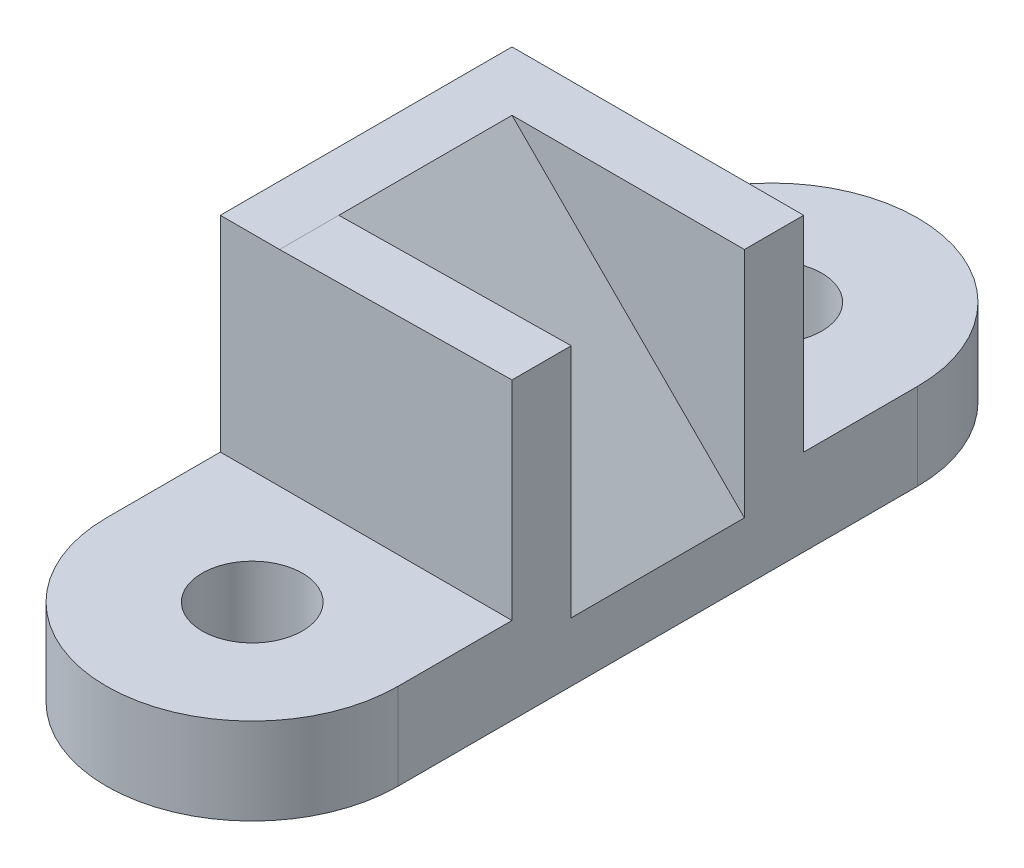
SolidWorks part; units mm, degrees
ref_plane "Front Plane" through (0, 0, 0) normal (0, 0, 1) x (1, 0, 0)
ref_plane "Top Plane" through (0, 0, 0) normal (0, 1, 0) x (1, 0, 0)
ref_plane "Right Plane" through (0, 0, 0) normal (1, 0, 0) x (0, 0, -1)
sketch "Sketch1" plane through (0, 0, 0) normal (0, 1, 0) x (1, 0, 0)
  line L0 (0, 0) -> (0, 114) construction
  line L1 (-32, 114) -> (-32, 0)
  line L2 (32, 114) -> (32, 0)
  arc A0 (-32, 0) -> (32, 0) centre (0, 0) ccw
  arc A1 (32, 114) -> (-32, 114) centre (0, 114) ccw
  point P1 (0, 0)
  dimension "D1" = 64
  dimension "D3" = 32
  dimension "D2" = 64
  dimension "D4" = 114
extrude "Boss-Extrude1" add sketch "Sketch1" along normal blind 19
sketch "Sketch2" plane through (0, 19, 0) normal (0, 1, 0) x (1, 0, 0)
  circle A0 centre (0, 0) radius 11
  dimension "D1" = 22
extrude "Cut-Extrude1" cut sketch "Sketch2" against normal blind 19
sketch "Sketch3" plane through (0, 19, 0) normal (0, 1, 0) x (1, 0, 0)
  circle A0 centre (0, 114) radius 11
  dimension "D1" = 22
extrude "Cut-Extrude3" cut sketch "Sketch3" against normal blind 422
sketch "Sketch4" plane through (0, 19, 0) normal (0, 1, 0) x (1, 0, 0)
  line L0 (0, 0) -> (0, 25) construction
  line L1 (-32, 114) -> (-32, 0) construction
  line L2 (-32, 25) -> (32, 25)
  line L3 (-32, 25) -> (-32, 89)
  line L4 (-32, 89) -> (32, 89)
  line L5 (32, 25) -> (32, 89)
  line L6 (32, 0) -> (32, 114) construction
  dimension "D1" = 25
extrude "Boss-Extrude2" add sketch "Sketch4" along normal blind 45
sketch "Sketch5" plane through (0, 0, -25) normal (0, 0, 1) x (1, 0, 0)
  line L0 (32, 64) -> (-19, 64)
  line L1 (-32, 64) -> (32, 64) construction
  line L2 (32, 64) -> (32, 13)
  line L3 (-19, 64) -> (32, 13)
extrude "Cut-Extrude4" cut sketch "Sketch5" against normal blind 51
sketch "Sketch6" plane through (0, 0, -25) normal (0, 0, 1) x (1, 0, 0)
  line L0 (32, 13) -> (32, 64.7094)
  line L1 (32, 64.7094) -> (-19, 64)
  line L2 (-19, 64) -> (32, 13)
extrude "Boss-Extrude3" add sketch "Sketch6" against normal blind 13
